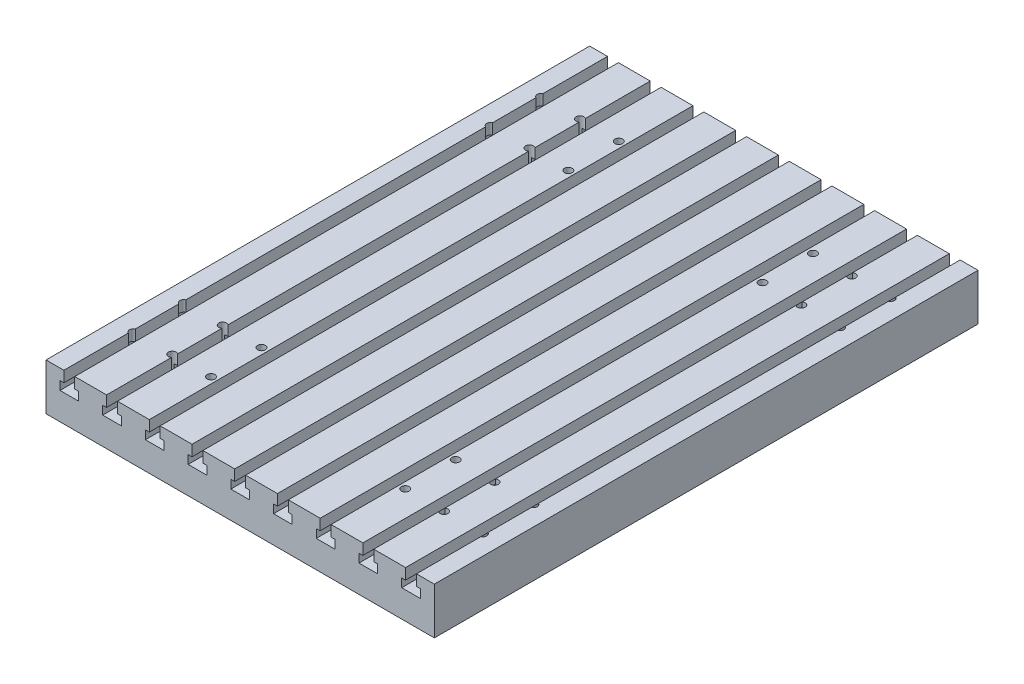
SolidWorks part; units mm, degrees
material "Plain Carbon Steel"
ref_plane "Front Plane" through (0, 0, 0) normal (0, 0, 1) x (1, 0, 0)
ref_plane "Top Plane" through (0, 0, 0) normal (0, 1, 0) x (1, 0, 0)
ref_plane "Right Plane" through (0, 0, 0) normal (1, 0, 0) x (0, 0, -1)
sketch "Sketch1" plane through (0, 0, 0) normal (0, 0, 1) x (1, 0, 0)
  line L1 (-250, -30) -> (250, -30)
  line L2 (-250, -30) -> (-250, 30)
  line L3 (-250, 30) -> (250, 30)
  line L4 (250, -30) -> (250, 30)
  line L5 (-250, -30) -> (250, 30) construction
  line L6 (-250, 30) -> (250, -30) construction
  point P0 (0, 0)
  dimension "D1" = 500
  dimension "D2" = 60
extrude "Boss-Extrude1" add sketch "Sketch1" along normal mid plane 700
sketch "Sketch2" plane through (0, 0, -350) normal (0, 0, -1) x (-1, 0, 0)
  line L0 (0, 30) -> (0, -30) construction
  line L1 (-250, 30) -> (250, 30) construction
  line L2 (250, -30) -> (-250, -30) construction
  line L3 (7, 16) -> (12, 16)
  line L4 (-7, 30) -> (7, 30)
  line L5 (-7, 30) -> (-7, 16)
  line L7 (7, 30) -> (7, 16)
  line L8 (-12, 16) -> (-7, 16)
  line L9 (-12, 16) -> (-12, 5)
  line L10 (-12, 5) -> (12, 5)
  line L11 (12, 16) -> (12, 5)
  point P14 (0, 5)
  point P17 (0, 30)
  dimension "D1" = 14
  dimension "D2" = 24
  dimension "D3" = 25
  dimension "D4" = 11
extrude "Cut-Extrude1" cut sketch "Sketch2" against normal up to next
pattern_linear "LPattern1" count 5 spacing 55 along (1, 0, 0) count 5 spacing 55 along (-1, 0, 0) of "Cut-Extrude1"
hole_wizard "CBORE for M5 Hex Socket Head Cap Screw1" positions "Sketch9" profile "Sketch6" counterbore size "M5" standard "ISO" end condition through all
sketch "Sketch9" plane through (0, 30, 0) normal (0, 1, 0) x (1, 0, 0)
  point P0 (225, 262.5)
  point P3 (175, 262.5)
  point P6 (125, 262.5)
  point P9 (125, 197.5)
  point P12 (175, 197.5)
  point P15 (225, 197.5)
sketch "Sketch6" plane through (225, 30, -262.5) normal (1, 0, 0) x (0, 0, 1)
  line L0 (0, 0) -> (0, 60)
  line L1 (0, 60) -> (2.75, 60)
  line L3 (2.75, 60) -> (2.75, 30.4)
  line L4 (2.75, 30.4) -> (5, 30.4)
  line L5 (5, 30.4) -> (5, 0)
  line L7 (5, 0) -> (0, 0)
  line L11 (0, -6.35) -> (0, 107.95) construction
  dimension "Thru Hole Dia." = 5.5
  dimension "Thru Hole Depth" = 60
  dimension "C'Bore Dia." = 10
  dimension "C'Bore Depth" = 30.4
mirror "Mirror1" about plane through (0, 0, 0) normal (1, 0, 0) of "CBORE for M5 Hex Socket Head Cap Screw1" second plane through (0, 0, 0) second plane normal (0, 0, 1)
